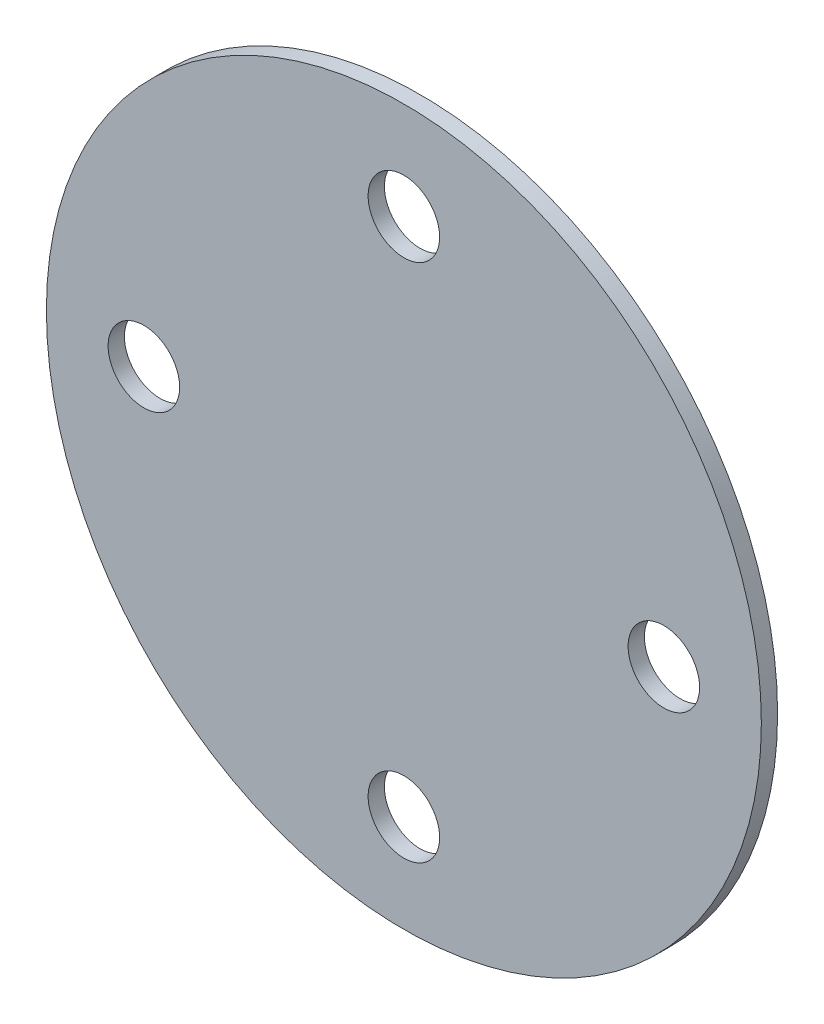
SolidWorks part; units mm, degrees
ref_plane "Plan de face" through (0, 0, 0) normal (0, 0, 1) x (1, 0, 0)
ref_plane "Plan de dessus" through (0, 0, 0) normal (0, 1, 0) x (1, 0, 0)
ref_plane "Plan de droite" through (0, 0, 0) normal (1, 0, 0) x (0, 0, -1)
sketch "Esquisse1" plane through (0, 0, 0) normal (0, 0, 1) x (1, 0, 0)
  circle A0 centre (0, 0) radius 11
  circle A1 centre (0, 8) radius 1.1
  circle A2 centre (8, 0) radius 1.1
  circle A3 centre (0, -8) radius 1.1
  circle A4 centre (-8, 0) radius 1.1
  point P14 (0, 0)
  dimension "D1" = 8
  dimension "D2" = 2.2
  dimension "D3" = 22
  dimension "D4" = 4
extrude "Boss.-Extru.1" add sketch "Esquisse1" along normal blind 0.5
